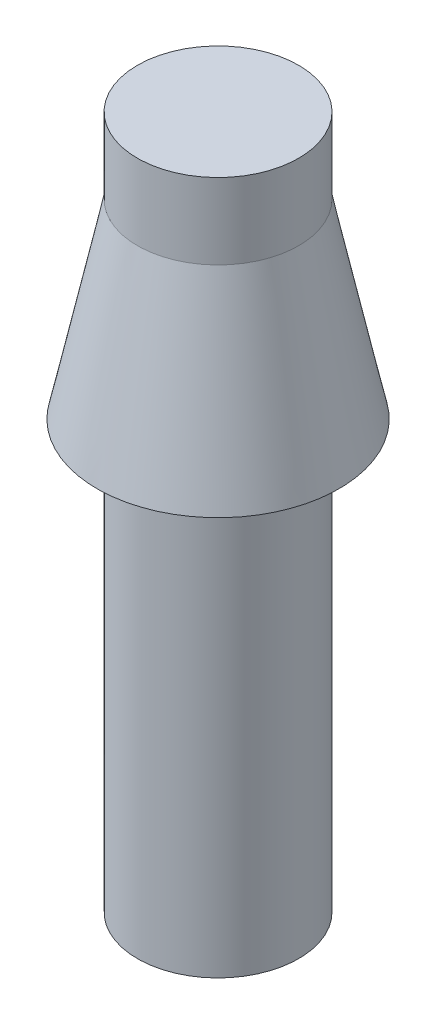
SolidWorks part; units mm, degrees
ref_plane "Front Plane" through (0, 0, 0) normal (0, 0, 1) x (1, 0, 0)
ref_plane "Top Plane" through (0, 0, 0) normal (0, 1, 0) x (1, 0, 0)
ref_plane "Right Plane" through (0, 0, 0) normal (1, 0, 0) x (0, 0, -1)
sketch "Sketch2" plane through (0, 0, 0) normal (0, 0, 1) x (1, 0, 0)
  line L0 (0, 0) -> (5, 0)
  line L1 (5, 0) -> (5, 26.5)
  line L2 (5, 26.5) -> (7.5082, 26.5)
  line L3 (7.5082, 26.5) -> (5, 38.3)
  line L6 (5, 38.3) -> (5, 43)
  line L7 (5, 43) -> (0, 43)
  line L8 (0, 43) -> (0, 0)
  line L9 (5, 38.3) -> (0, 38.3)
  point P6 (7.5082, 4.5375)
  point P10 (7.5082, 14.4331)
  dimension "D1" = 5
  dimension "D2" = 5
  dimension "D3" = 12
  dimension "D4" = 4.7
  dimension "D5" = 11.8
  dimension "D6" = 26.5
revolve "Revolve1" add sketch "Sketch2" angle 360 about L8
